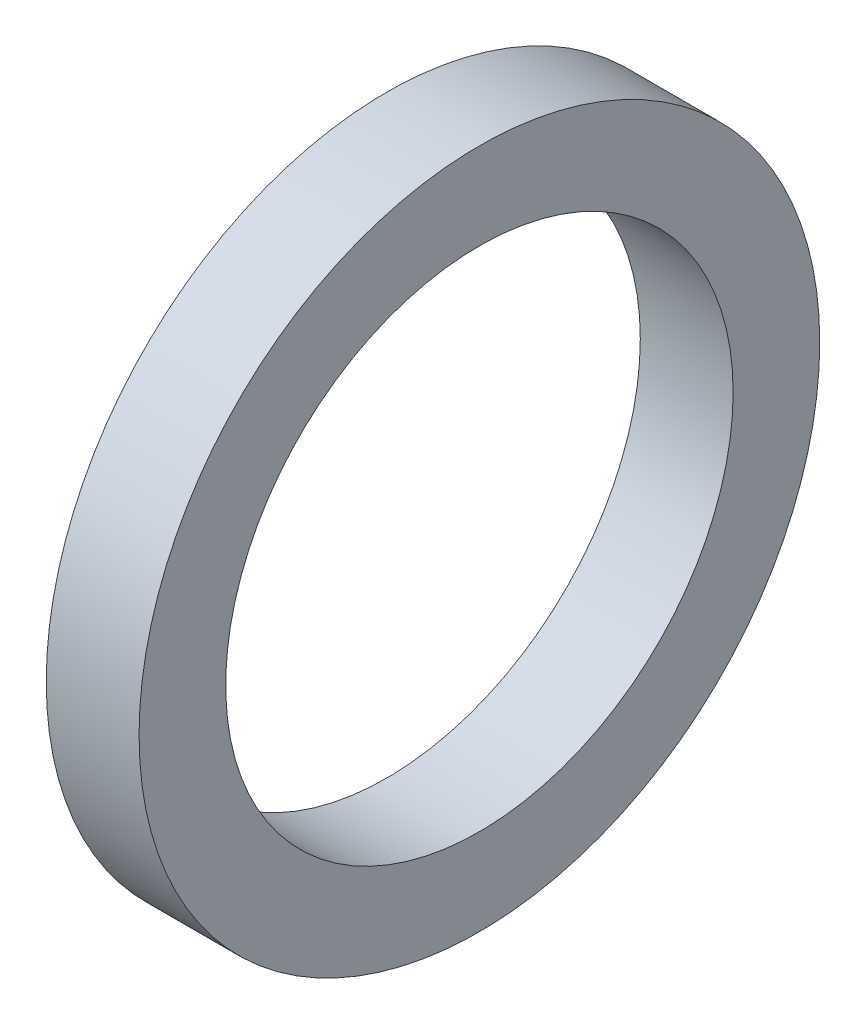
SolidWorks part; units mm, degrees
ref_plane "Front Plane" through (0, 0, 0) normal (0, 0, 1) x (1, 0, 0)
ref_plane "Top Plane" through (0, 0, 0) normal (0, 1, 0) x (1, 0, 0)
ref_plane "Right Plane" through (0, 0, 0) normal (1, 0, 0) x (0, 0, -1)
sketch "Sketch1" plane through (0, 0, 0) normal (1, 0, 0) x (0, 0, -1)
  circle A0 centre (0, 0) radius 5.5
  circle A1 centre (0, 0) radius 4.1
  dimension "D1" = 11
  dimension "D2" = 8.2
extrude "Boss-Extrude1" add sketch "Sketch1" along normal blind 1.5
